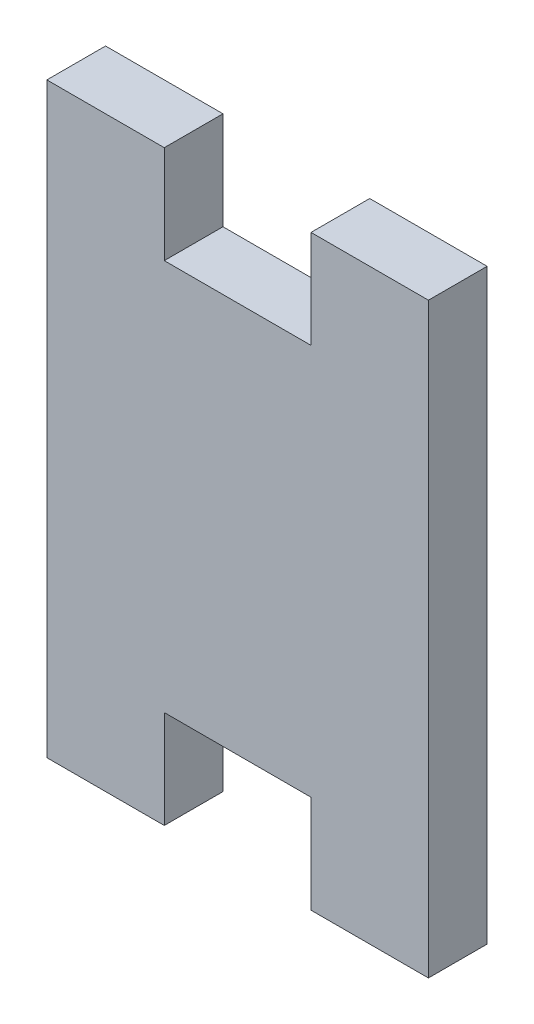
SolidWorks part; units mm, degrees
ref_plane "Plano frontal" through (0, 0, 0) normal (0, 0, 1) x (1, 0, 0)
ref_plane "Plano superior" through (0, 0, 0) normal (0, 1, 0) x (1, 0, 0)
ref_plane "Plano direito" through (0, 0, 0) normal (1, 0, 0) x (0, 0, -1)
sketch "Esboço1" plane through (0, 0, 0) normal (0, 0, 1) x (1, 0, 0)
  line L0 (9.75, -85.2285) -> (9.75, -60.2285)
  line L1 (-9.75, -85.2285) -> (-3.75, -85.2285)
  line L2 (-3.75, -60.2285) -> (3.75, -60.2285)
  line L3 (-9.75, -60.2285) -> (-9.75, -85.2285)
  line L5 (-9.75, -60.2285) -> (-9.75, -55.2285)
  line L6 (-9.75, -55.2285) -> (-3.75, -55.2285)
  line L7 (-3.75, -80.2285) -> (-3.75, -85.2285)
  line L8 (-3.75, -55.2285) -> (-3.75, -60.2285)
  line L9 (3.75, -80.2285) -> (3.75, -85.2285)
  line L10 (3.75, -85.2285) -> (9.75, -85.2285)
  line L11 (-3.75, -80.2285) -> (3.75, -80.2285)
  line L12 (9.75, -60.2285) -> (9.75, -55.2285)
  line L13 (9.75, -55.2285) -> (3.75, -55.2285)
  line L14 (3.75, -55.2285) -> (3.75, -60.2285)
extrude "Ressalto-extrusão1" add sketch "Esboço1" along normal blind 3
